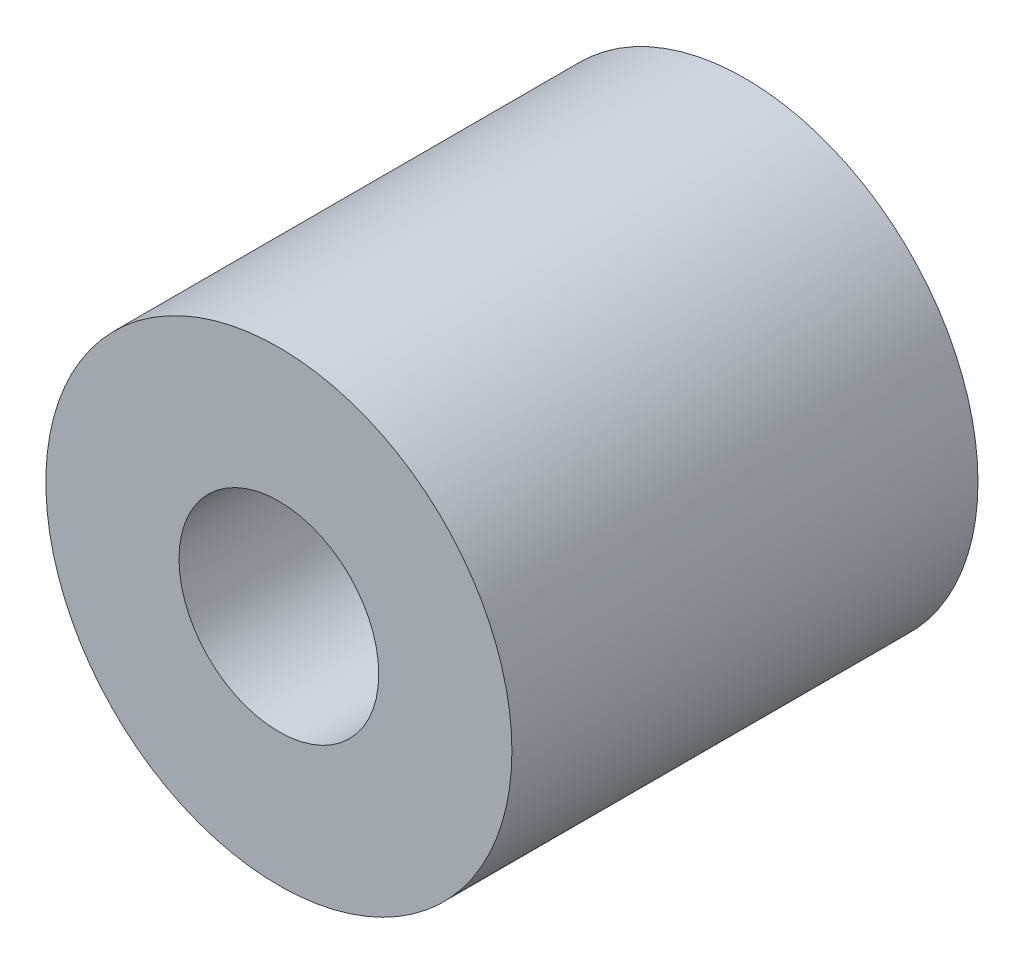
SolidWorks part; units mm, degrees
ref_plane "前视基准面" through (0, 0, 0) normal (0, 0, 1) x (1, 0, 0)
ref_plane "上视基准面" through (0, 0, 0) normal (0, 1, 0) x (1, 0, 0)
ref_plane "右视基准面" through (0, 0, 0) normal (1, 0, 0) x (0, 0, -1)
sketch "草图1" plane through (0, 0, 0) normal (0, 0, 1) x (1, 0, 0)
  circle A0 centre (0, 0) radius 3.5
  circle A1 centre (0, 0) radius 1.5
  dimension "D1" = 7
  dimension "D2" = 3
extrude "凸台-拉伸1" add sketch "草图1" along normal blind 7
